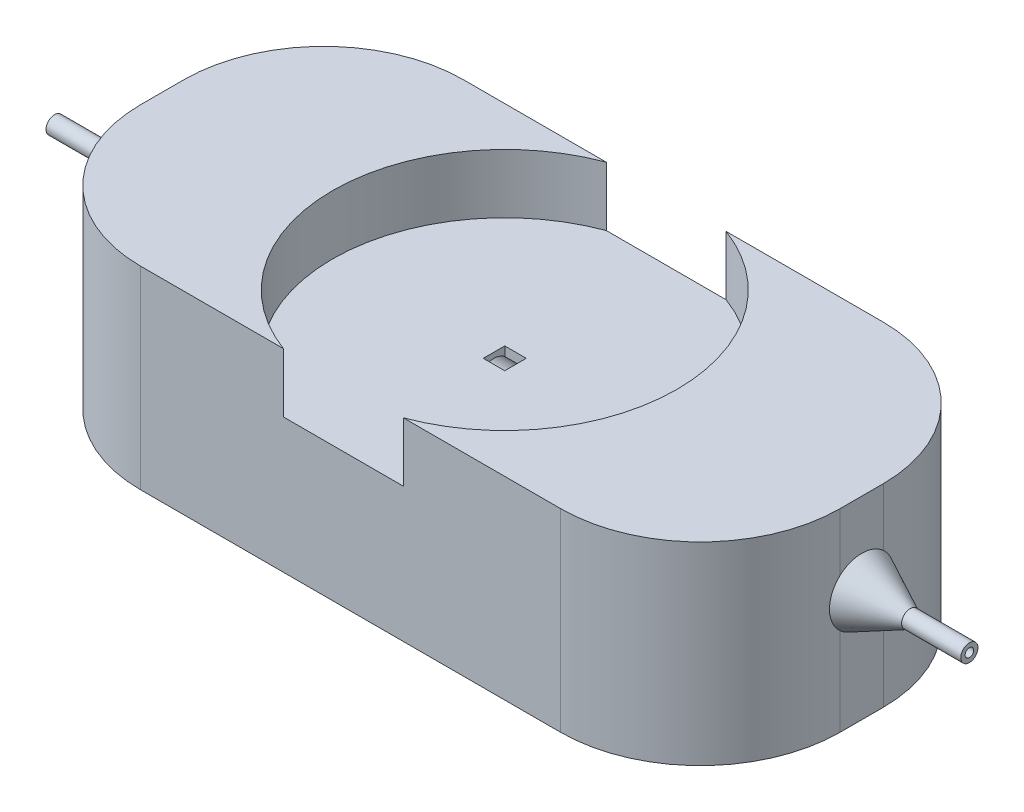
SolidWorks part; units mm, degrees
ref_plane "Front Plane" through (0, 0, 0) normal (0, 0, 1) x (1, 0, 0)
ref_plane "Top Plane" through (0, 0, 0) normal (0, 1, 0) x (1, 0, 0)
ref_plane "Right Plane" through (0, 0, 0) normal (1, 0, 0) x (0, 0, -1)
sketch "Sketch1" plane through (0, 0, 0) normal (0, 1, 0) x (1, 0, 0)
  line L1 (-25, -15) -> (40, -15)
  line L2 (-25, -15) -> (-25, 15)
  line L3 (-25, 15) -> (40, 15)
  line L4 (40, -15) -> (40, 15)
  line L5 (-25, -15) -> (40, 15) construction
  line L6 (-25, 15) -> (40, -15) construction
  point P0 (0, 0)
  dimension "D1" = 30
  dimension "D2" = 65
extrude "Boss-Extrude1" add sketch "Sketch1" along normal blind 58
sketch "Sketch3" plane through (-25, 0, 0) normal (-1, 0, 0) x (0, 0, 1)
  line L0 (-15, 58) -> (15, 58) construction
  circle A0 centre (0, 50.4) radius 1.6
  dimension "D1" = 3.2
  dimension "D2" = 7.6
fillet "Fillet1" radius 13 4 edges at (40, 29, -15) (-25, 29, -15) (40, 29, 15) (-25, 29, 15)
ref_plane "Plane2" through (0, -10, 0) normal (0, -1, 0) x (-1, 0, 0)
sketch "Sketch15" plane through (0, -10, 0) normal (0, -1, 0) x (-1, 0, 0)
  line L1 (-41.9055, 15.8797) -> (41.7906, 15.8797)
  line L2 (-41.9055, 15.8797) -> (-41.9055, -15.8187)
  line L3 (-41.9055, -15.8187) -> (41.7906, -15.8187)
  line L4 (41.7906, 15.8797) -> (41.7906, -15.8187)
extrude "Cut-Extrude7" cut sketch "Sketch15" against normal blind 50
ref_plane "Plane3" through (0, 40, 0) normal (0, -1, 0) x (-1, 0, 0)
ref_plane "Plane4" through (0, 58, 0) normal (0, 1, 0) x (1, 0, 0)
sketch "Sketch18" plane through (0, 58, 0) normal (0, 1, 0) x (1, 0, 0)
  circle A0 centre (6.8285, 0) radius 16
  dimension "D1" = 32
extrude "Cut-Extrude10" cut sketch "Sketch18" against normal blind 5.5
extrude "Cut-Extrude12" cut sketch "Sketch3" against normal up to next
ref_plane "Plane5" through (0, 52.5, 0) normal (0, 1, 0) x (1, 0, 0)
sketch "Sketch21" plane through (0, 52.5, 0) normal (0, 1, 0) x (1, 0, 0)
  line L1 (5.8285, -1) -> (7.8285, -1)
  line L2 (5.8285, -1) -> (5.8285, 1)
  line L3 (5.8285, 1) -> (7.8285, 1)
  line L4 (7.8285, -1) -> (7.8285, 1)
  line L5 (5.8285, -1) -> (7.8285, 1) construction
  line L6 (5.8285, 1) -> (7.8285, -1) construction
  point P0 (6.8285, 0)
  point P6 (0, 0)
  dimension "D1" = 2
  dimension "D2" = 2
extrude "Cut-Extrude13" cut sketch "Sketch21" against normal blind 8
ref_plane "Plane7" through (-25, 0, 0) normal (-1, 0, 0) x (0, 0, 1)
sketch "Sketch24" plane through (0, 0, 0) normal (0, 0, 1) x (1, 0, 0)
  line L1 (-25, 52) -> (-25, 48.8) construction
  line L5 (-25, 50.4) -> (-31.2466, 50.4) construction
  line L7 (-25, 50.4) -> (46.09, 50.4) construction
  line L8 (-25, 50.8) -> (-35, 50.8)
  line L9 (-29.5, 51.2) -> (-35, 51.2)
  line L10 (-35, 51.2) -> (-35, 50.8)
  line L11 (-25, 40) -> (-25, 58) construction
  line L12 (-29.5, 51.2) -> (-25, 53.4)
  line L13 (-25, 50.8) -> (-25, 53.4)
  dimension "D1" = 0.4
  dimension "D2" = 6
  dimension "D3" = 0.8
  dimension "D4" = 10
  dimension "D5" = 4.5
revolve "Revolve1" add sketch "Sketch24" angle 360 about L5
sketch "Sketch25" plane through (0, 0, 0) normal (0, 0, 1) x (1, 0, 0)
  line L1 (50.4822, 50.3986) -> (44.2356, 50.3986) construction
  line L13 (40, 50.7986) -> (40, 53.3986)
  line L14 (40, 58) -> (40, 40) construction
  line L15 (40, 53.3986) -> (44.5, 51.1986)
  line L16 (44.5, 51.1986) -> (50, 51.1986)
  line L17 (50, 51.1986) -> (50, 50.7986)
  line L18 (50, 50.7986) -> (40, 50.7986)
  dimension "D1" = 0.4
  dimension "D2" = 0.8
  dimension "D3" = 10
  dimension "D4" = 6
  dimension "D5" = 4.5
revolve "Revolve2" add sketch "Sketch25" angle 360 about L1
